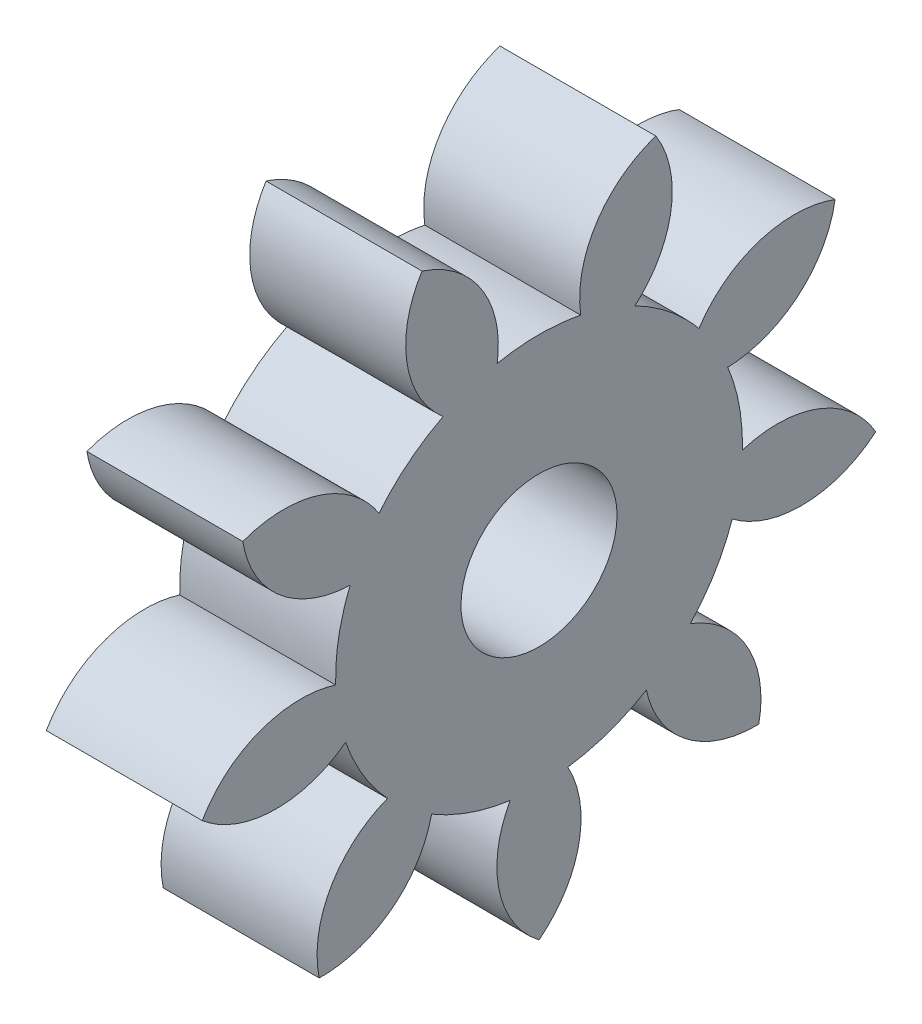
SolidWorks part; units mm, degrees
ref_plane "Plane1" through (0, 0, 0) normal (0, 0, 1) x (1, 0, 0)
ref_plane "Plane2" through (0, 0, 0) normal (0, 1, 0) x (1, 0, 0)
ref_plane "Plane3" through (0, 0, 0) normal (1, 0, 0) x (0, 0, -1)
sketch "HoldingSke" plane through (0, 0, 0) normal (0, 1, 0) x (1, 0, 0)
  line L0 (0, 0) -> (500.2823, -88.2133)
  line L1 (-15, 0) -> (100, 0) construction
  line L2 (0, 0) -> (-2.1039, 2.3779)
  line L3 (0, 0) -> (-11.863, 4.5341)
  line L4 (0, 0) -> (8.5048, 1.4996)
  line L5 (0, 0) -> (-47.5972, -17.7524)
  line L6 (0, 0) -> (-2.632, -1.7758)
  line L7 (-2.1039, 2.3779) -> (8.8308, 51.9871)
  line L8 (-76.2, 54.61) -> (-72.771, 54.61)
  line L9 (-71.009, 38.7566) -> (-53.1078, 45.2721)
  line L10 (-76.2, 71.12) -> (104.1128, 71.12)
  line L11 (0, 0) -> (-3.175, 0)
  line L12 (-76.2, 101.6) -> (-76.1492, 101.6)
  line L13 (24.9733, 27.94) -> (52.9518, 28.4284)
  line L14 (24.9733, 27.94) -> (25.0241, 27.9398)
  line L15 (24.9733, 27.94) -> (100.4021, 29.52)
  circle A0 centre (0, 0) radius 1.5875
  circle A1 centre (0, 0) radius 4.1402
  circle A2 centre (0, 0) radius 38.1
  circle A3 centre (0, 0) radius 1.5875
  dimension "MHD" = 8.2804
  dimension "Hub_dia" = 76.2
  dimension "Bore" = 3.175
  dimension "MBD" = 3.175
  dimension "Num_teeth" = 10
  dimension "Pitch_radius" = 180.3128
  dimension "Pitch" = 508
  dimension "Width" = 3.175
  dimension "Overall_len" = 50.8
  dimension "Show_teeth" = 10
  dimension "Thickness" = 3.175
  dimension "OAL" = 50.8001
  dimension "T_dim" = 3.429
  dimension "Ap" = 20
  dimension "H" = 19.05
  dimension "Backlash" = 0.0508
  dimension "Addendum_fac" = 1
  dimension "Dedendum_fac" = 1.2
  dimension "Clearance_fac" = 0.2
  dimension "Dedendum_add" = 0.0508
sketch "BasProSke" plane through (0, 0, 0) normal (0, 1, 0) x (1, 0, 0)
  line L0 (-10, 0) -> (60, 0) construction
  line L1 (0, 0) -> (0, 6.985)
  line L2 (0, 0) -> (3.175, 0)
  line L3 (3.175, 0) -> (3.175, 6.985)
  line L4 (3.175, 6.985) -> (0, 6.985)
  dimension "Diameter" = 13.97
  dimension "Thickness" = 3.175
revolve "Base-Revolve" add sketch "BasProSke" angle 360 about L0
sketch "TooCutSke" plane through (0, 0, 0) normal (1, 0, 0) x (0, 0, -1)
  line L1 (0, 0) -> (0, 107) construction
  line L2 (0, 0) -> (-1.1786, 5.5922) construction
  line L3 (0, 0) -> (-3.8703, 10.6336) construction
  line L4 (-1.1786, 5.5922) -> (-1.9352, 5.3168) construction
  arc A0 (0.8509, 4.0518) -> (-0.8509, 4.0518) centre (0, 0) ccw
  arc A1 (2.4581, 6.5653) -> (-2.4581, 6.5653) centre (0, 0) ccw
  circle A2 centre (0, 0) radius 5.715 construction
  circle A3 centre (0, 0) radius 5.3703 construction
  arc A4 (-0.8509, 4.0518) -> (-2.4581, 6.5653) centre (-3.1139, 4.3754) ccw
  arc A5 (2.4581, 6.5653) -> (0.8509, 4.0518) centre (3.1139, 4.3754) ccw
  dimension "Root_dia" = 8.2804
  dimension "Overcut_dia" = 14.0208
  dimension "Pitch_dia" = 11.43
  dimension "Base_dia" = 10.7407
  dimension "Flank_rad" = 2.286
  dimension "Half_ang" = 20
  dimension "Half_CT" = 0.8051
extrude "ToothCut" cut sketch "TooCutSke" along normal through all
fillet "Breaks" [suppressed] radius 0.0254
fillet "RootFillets" [suppressed] radius 0.3048
pattern_circular "TeethCuts" count 10 every 40 about axis through (-10, 0, 0) along (1, 0, 0) of "ToothCut"
sketch "HubNeaOneSke" plane through (0, 0, 0) normal (-1, 0, 0) x (0, 0, 1)
  circle A0 centre (0, 0) radius 4.1402
  dimension "Diameter" = 8.2804
extrude "HubNearOne" [suppressed] add sketch "HubNeaOneSke" along normal blind 47.6251
sketch "HubNeaBotSke" plane through (0, 0, 0) normal (-1, 0, 0) x (0, 0, 1)
  circle A0 centre (0, 0) radius 4.1402
  dimension "Diameter" = 8.2804
extrude "HubNearBoth" [suppressed] add sketch "HubNeaBotSke" along normal blind 23.8125
ref_plane "FarPln" through (3.175, 0, 0) normal (1, 0, 0) x (0, 0, -1)
sketch "HubFarSke" plane through (3.175, 0, 0) normal (1, 0, 0) x (0, 0, -1)
  circle A0 centre (0, 0) radius 4.1402
  dimension "Diameter" = 8.2804
extrude "HubFar" [suppressed] add sketch "HubFarSke" along normal blind 23.8125
sketch "BorSke" plane through (0, 0, 0) normal (1, 0, 0) x (0, 0, -1)
  circle A0 centre (0, 0) radius 1.5875
  dimension "Diameter" = 3.175
extrude "Bore" cut sketch "BorSke" along normal mid plane 101.6001
sketch "KeySke" plane through (0, 0, 0) normal (1, 0, 0) x (0, 0, -1)
  line L0 (-0.127, 0) -> (-0.127, 1.8415)
  line L1 (-0.127, 1.8415) -> (0.127, 1.8415)
  line L2 (0.127, 1.8415) -> (0.127, 0)
  line L3 (0, 0) -> (0, 34) construction
  line L4 (-0.127, 0) -> (0.127, 0)
  dimension "Offset" = 1.8415
  dimension "Width" = 0.254
extrude "Keyway" [suppressed] cut sketch "KeySke" along normal mid plane 101.6001
pattern_circular "Keyway2" [suppressed] count 2 every 90 about axis through (-10, 0, 0) along (1, 0, 0)
scale "Scale1" scale about centroid uniform scaling no x scale factor 1.3 y scale factor 1.25 z scale factor 1.3
equation "' \"Pitch@HoldingSke\" = 4"
equation "' \"Num_teeth@HoldingSke\" = 12"
equation "' \"Ap@HoldingSke\" =  20"
equation "' \"Width@HoldingSke\" = 0.5"
equation "' \"Hub_dia@HoldingSke\"= 1"
equation "' \"Overall_len@HoldingSke\" = 1.0"
equation "' \"Bore@HoldingSke\" = 0.75"
equation "' \"T_dim@HoldingSke\" = 0.85"
equation "' \"Width@KeySke\" = 0.25"
equation "' \"Show_teeth@HoldingSke\" = 13"
equation "' \"Backlash@HoldingSke\" = 0.009"
equation "' \"Addendum_fac@HoldingSke\" = 1.0"
equation "' \"Dedendum_fac@HoldingSke\" = 1.25"
equation "' \"Dedendum_add@HoldingSke\" = 0.00005"
equation "' \"Clearance_fac@HoldingSke\" = 0.25"
equation "' \"Pitch@HoldingSke\" = 0.5"
equation "' \"Num_teeth@HoldingSke\" = 23"
equation "' \"Show_teeth@HoldingSke\" = 23"
equation "' \"Backlash@HoldingSke\" = 0.0375"
equation "\"Overcut_dia@TooCutSke\"=(9 + 2 * \"Addendum_fac@HoldingSke\") / \"Pitch@HoldingSke\" + 0.002"
equation "\"Pitch_dia@TooCutSke\"=9/ \"Pitch@HoldingSke\""
equation "\"Base_dia@TooCutSke\"=9 / \"Pitch@HoldingSke\" * cos((\"Ap@HoldingSke\"  * 3.14159265 / 180))"
equation "\"Root_dia@TooCutSke\"=(9 + 2) / \"Pitch@HoldingSke\" - 2 * (\"Addendum_fac@HoldingSke\" + \"Dedendum_fac@HoldingSke\") / \"Pitch@HoldingSke\" - \"Dedendum_add@HoldingSke\" * 2"
equation "\"Half_ang@TooCutSke\"=180 / 9"
equation "\"Half_CT@TooCutSke\"=9 / \"Pitch@HoldingSke\" * sin((3.14159265 / 2 / \"Num_teeth@HoldingSke\")) / 2 - 7 * \"Backlash@HoldingSke\" / 4"
equation "\"Flank_rad@TooCutSke\"=9/ \"Pitch@HoldingSke\" / 5"
equation "\"Radius@RootFillets\" = \"Clearance_fac@HoldingSke\" / \"Pitch@HoldingSke\" + \"Dedendum_add@HoldingSke\""
equation "\"Break_rad@Breaks\" = 0.02 / \"Pitch@HoldingSke\""
equation "\"Thickness@HoldingSke\" = \"Width@HoldingSke\""
equation "\"OAL@HoldingSke\" = \"Thickness@HoldingSke\""
equation "\"MHD@HoldingSke\" = (\"Num_teeth@HoldingSke\" + 2) / \"Pitch@HoldingSke\" - 2 * (\"Addendum_fac@HoldingSke\" + \"Dedendum_fac@HoldingSke\")  / \"Pitch@HoldingSke\" - \"Dedendum_add@HoldingSke\" * 2"
equation "\"MBD@HoldingSke\" = (\"Num_teeth@HoldingSke\" + 2) / \"Pitch@HoldingSke\" - 2 * (\"Addendum_fac@HoldingSke\" + \"Dedendum_fac@HoldingSke\")  / \"Pitch@HoldingSke\" - \"Dedendum_add@HoldingSke\" * 2 - 0.002"
equation "\"MHD@HoldingSke\" = ((sgn( \"MHD@HoldingSke\" - \"Hub_dia@HoldingSke\" )-1)*( \"MHD@HoldingSke\" - \"Hub_dia@HoldingSke\" ))/-2+ \"Hub_dia@HoldingSke\""
equation "\"MBD@HoldingSke\" = ((sgn( \"MBD@HoldingSke\" - \"Bore@HoldingSke\" )-1)*( \"MBD@HoldingSke\" - \"Bore@HoldingSke\" ))/-2+ \"Bore@HoldingSke\""
equation "\"OAL@HoldingSke\" = ((sgn( \"OAL@HoldingSke\" - \"Overall_len@HoldingSke\" )+1)*( \"OAL@HoldingSke\" - \"Overall_len@HoldingSke\" ))/2 + \"Overall_len@HoldingSke\" + 0.000002"
equation "\"Num_teeth@TeethCuts\"=int( 9 ) + 1"
equation "\"Num_teeth@TeethCuts\" = ((sgn( \"Num_teeth@TeethCuts\" - \"Num_teeth@HoldingSke\" )-1)*( \"Num_teeth@TeethCuts\" - \"Num_teeth@HoldingSke\" ))/-2+ \"Num_teeth@HoldingSke\""
equation "\"Num_teeth@TeethCuts\" = ((sgn( \"Num_teeth@TeethCuts\" - 2.0)+1)*( \"Num_teeth@TeethCuts\" - 2.0))/2 +2.0"
equation "\"Angle@TeethCuts\"=360.0 / 9"
equation "\"Diameter@BasProSke\"=(9 + 2 * \"Addendum_fac@HoldingSke\") / \"Pitch@HoldingSke\""
equation "\"Thickness@BasProSke\"=.125"
equation "' \"Fillet_rad@BasProSke\" =  \"Thickness@HoldingSke\" * 0.05"
equation "\"MHD@HoldingSke\" = ((sgn( \"MHD@HoldingSke\" - \"Root_dia@TooCutSke\" )-1)*( \"MHD@HoldingSke\" - \"Root_dia@TooCutSke\" ))/-2+ \"Root_dia@TooCutSke\""
equation "\"Diameter@HubNeaOneSke\" = \"MHD@HoldingSke\""
equation "\"Length@HubNearOne\" = \"OAL@HoldingSke\" - \"Thickness@BasProSke\""
equation "\"Diameter@HubNeaBotSke\" = \"MHD@HoldingSke\""
equation "\"Length@HubNearBoth\" = ( \"OAL@HoldingSke\" - \"Thickness@BasProSke\" ) / 2.0"
equation "\"Thickness@FarPln\" = \"Thickness@BasProSke\""
equation "\"Diameter@HubFarSke\" = \"MHD@HoldingSke\""
equation "\"Length@HubFar\" = ( \"OAL@HoldingSke\" - \"Thickness@BasProSke\" ) / 2.0"
equation "\"Diameter@BorSke\" = \"MBD@HoldingSke\""
equation "\"D1@Bore\" = \"OAL@HoldingSke\" * 2.0"
equation "\"D1@Keyway\" = \"OAL@HoldingSke\" * 2.0"
equation "\"Offset@KeySke\" = \"T_dim@HoldingSke\" - \"MBD@HoldingSke\" / 2.0"
